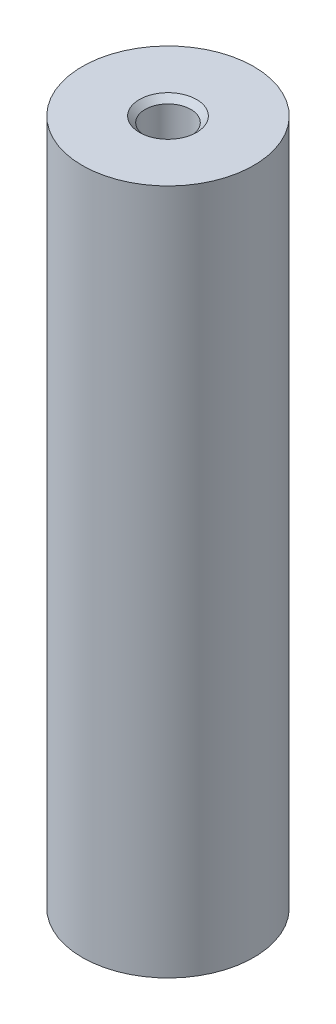
SolidWorks part; units mm, degrees
ref_plane "Front Plane" through (0, 0, 0) normal (0, 0, 1) x (1, 0, 0)
ref_plane "Top Plane" through (0, 0, 0) normal (0, 1, 0) x (1, 0, 0)
ref_plane "Right Plane" through (0, 0, 0) normal (1, 0, 0) x (0, 0, -1)
sketch "Sketch1" plane through (0, 0, 0) normal (0, 1, 0) x (1, 0, 0)
  circle A0 centre (0, 0) radius 7.5
  dimension "D1" = 15
extrude "Boss-Extrude1" add sketch "Sketch1" along normal blind 60
sketch "Sketch2" plane through (0, 60, 0) normal (0, 1, 0) x (1, 0, 0)
  circle A0 centre (0, 0) radius 2
  dimension "D1" = 4
extrude "Cut-Extrude1" cut sketch "Sketch2" against normal blind 5
chamfer "Chamfer1" distance 0.5 angle 45 1 edges at (0, 60, 2)
sketch "Sketch3" plane through (0, 0, 0) normal (0, -1, 0) x (1, 0, 0)
  circle A0 centre (0, 0) radius 2
  dimension "D1" = 4
extrude "Cut-Extrude2" cut sketch "Sketch3" against normal blind 5
chamfer "Chamfer2" distance 0.5 angle 45 1 edges at (0, 0, -2)
